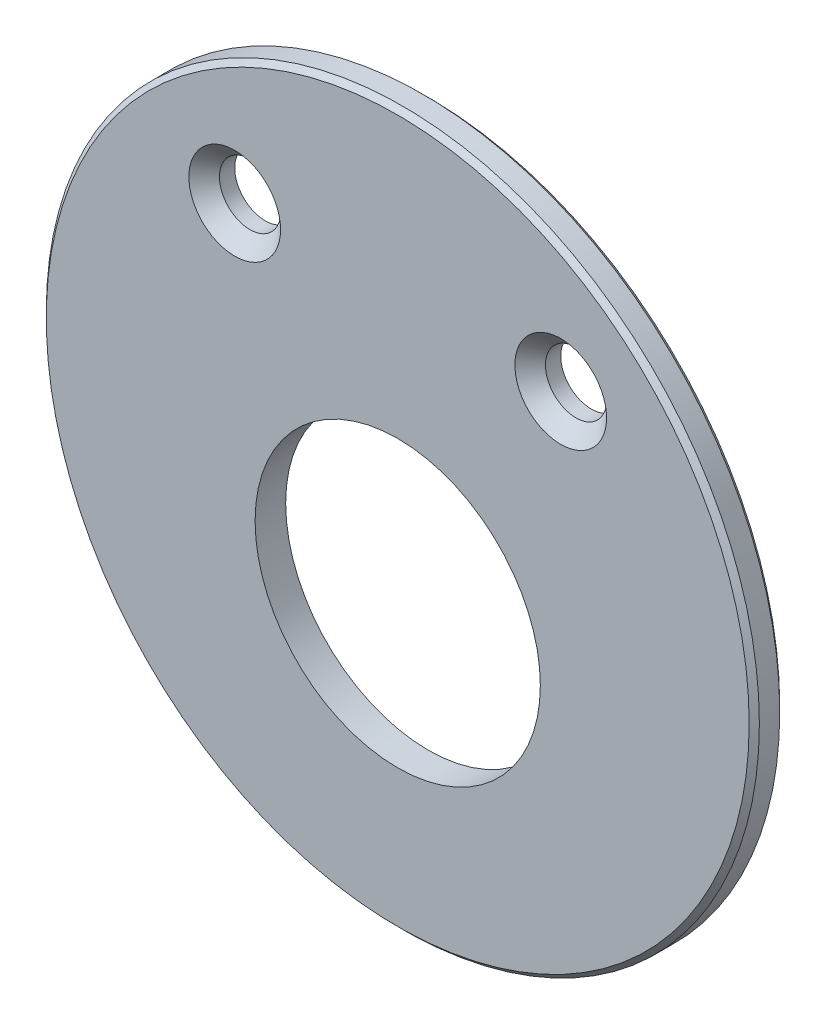
SolidWorks part; units mm, degrees
ref_plane "Front Plane" through (0, 0, 0) normal (0, 0, 1) x (1, 0, 0)
ref_plane "Top Plane" through (0, 0, 0) normal (0, 1, 0) x (1, 0, 0)
ref_plane "Right Plane" through (0, 0, 0) normal (1, 0, 0) x (0, 0, -1)
sketch "Sketch1" plane through (0, 0, 0) normal (0, 0, 1) x (1, 0, 0)
  circle A0 centre (0, 0) radius 17.5
  dimension "D1" = 35
extrude "Boss-Extrude1" add sketch "Sketch1" along normal blind 1.5
sketch "Sketch2" plane through (0, 0, 1.5) normal (0, 0, 1) x (1, 0, 0)
  circle A0 centre (0, -3.5) radius 7
  circle A1 centre (-8, 9.5) radius 1.5
  circle A2 centre (8, 9.5) radius 1.5
  dimension "D1" = 14
  dimension "D6" = 3
  dimension "D7" = 3
  dimension "D2" = 3.5
  dimension "D3" = 8
  dimension "D4" = 8
  dimension "D5" = 9.5
extrude "Cut-Extrude1" cut sketch "Sketch2" against normal blind 1.5
chamfer "Chamfer1" distance 0.75 angle 45 2 edges at (9.5, 9.5, 1.5) (-6.5, 9.5, 1.5)
chamfer "Chamfer2" distance 0.25 angle 45 2 edges at (17.5, 0, 0) (17.5, 0, 1.5)
